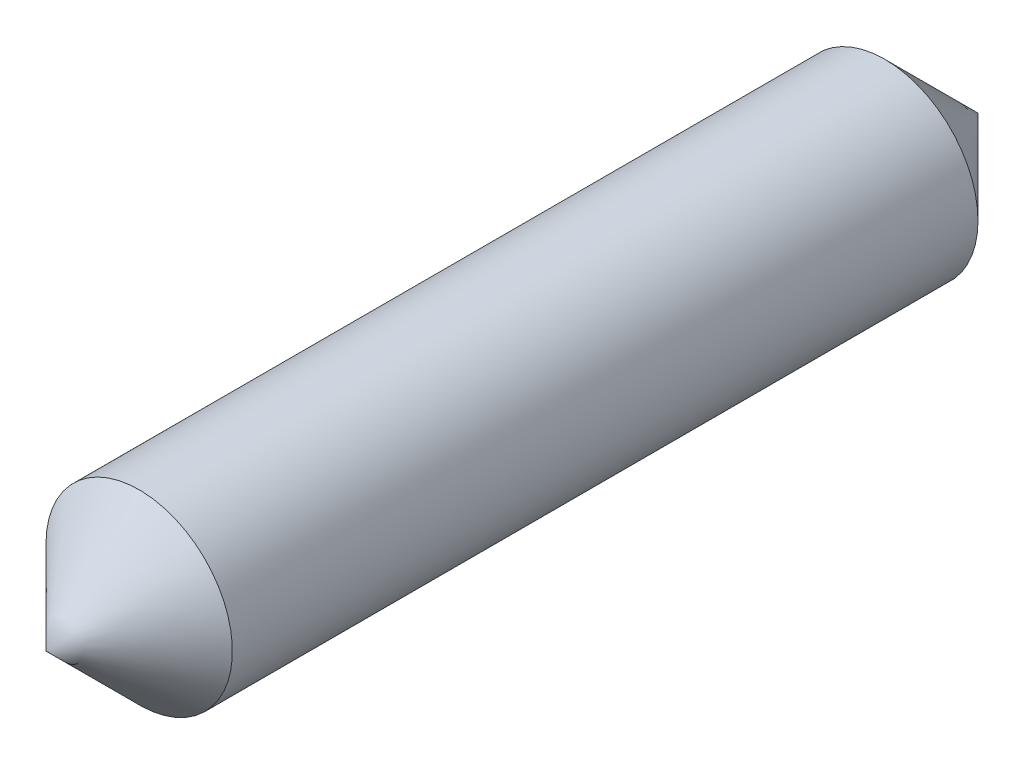
SolidWorks part; units mm, degrees
ref_plane "Front Plane" through (0, 0, 0) normal (0, 0, 1) x (1, 0, 0)
ref_plane "Top Plane" through (0, 0, 0) normal (0, 1, 0) x (1, 0, 0)
ref_plane "Right Plane" through (0, 0, 0) normal (1, 0, 0) x (0, 0, -1)
sketch "Sketch4" plane through (0, 0, 0) normal (0, 1, 0) x (1, 0, 0)
  line L0 (0, 50) -> (0, -50)
  line L1 (0, -50) -> (10, -40)
  line L2 (10, -40) -> (10, 40)
  line L3 (10, 0) -> (0, 0) construction
  line L4 (0, 50) -> (10, 40)
  dimension "D1" = 50
  dimension "D2" = 10
  dimension "D3" = 10
revolve "Revolve2" add sketch "Sketch4" angle 360 about L0
